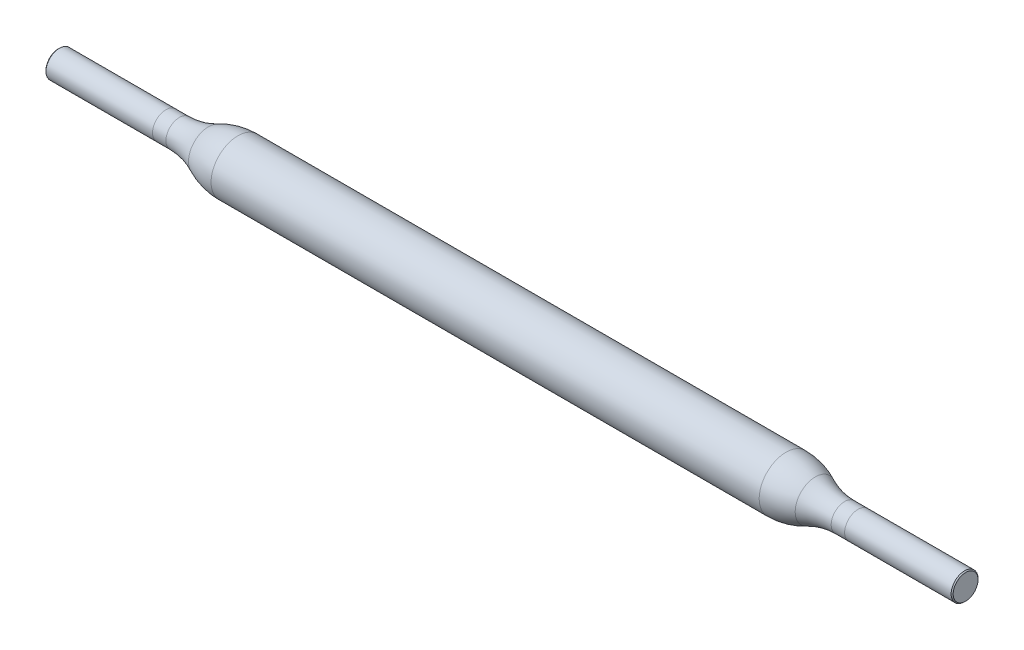
SolidWorks part; units mm, degrees
ref_plane "Front Plane" through (0, 0, 0) normal (0, 0, 1) x (1, 0, 0)
ref_plane "Top Plane" through (0, 0, 0) normal (0, 1, 0) x (1, 0, 0)
ref_plane "Right Plane" through (0, 0, 0) normal (1, 0, 0) x (0, 0, -1)
sketch "Sketch1" plane through (0, 0, 0) normal (0, 0, 1) x (1, 0, 0)
  line L0 (-33.75, 0) -> (33.75, 0)
  line L1 (33.75, 0) -> (33.75, 1)
  line L2 (-33.75, 0) -> (-33.75, 1)
  line L3 (-33.75, 1) -> (-24.75, 1)
  line L4 (-20.3911, 2) -> (20.3911, 2)
  line L5 (33.75, 1) -> (24.75, 1)
  line L6 (0, 0) -> (0, 10.5856) construction
  arc A0 (-24.75, 1) -> (-22.5706, 1.5) centre (-24.75, 6) ccw
  arc A1 (-20.3911, 2) -> (-22.5706, 1.5) centre (-20.3911, -3) ccw
  arc A2 (20.3911, 2) -> (22.5706, 1.5) centre (20.3911, -3) cw
  arc A3 (24.75, 1) -> (22.5706, 1.5) centre (24.75, 6) cw
  point P2 (0, 0)
  point P9 (0, 2)
  point P14 (-21.75, 2)
  dimension "D6" = 5
  dimension "D1" = 67.5
  dimension "D2" = 1
  dimension "D3" = 9
  dimension "D4" = 2
  dimension "D5" = 3
revolve "Revolve1" add sketch "Sketch1" angle 360 about L0
sketch "Sketch2" plane through (0, 0, 0) normal (0, 0, 1) x (1, 0, 0)
  line L0 (-25.75, 3.4753) -> (-25.75, -4.3442)
  line L1 (25.75, 4.2201) -> (25.75, -4.3442)
  line L2 (-33.75, 1) -> (-33.75, -1) construction
  line L3 (33.75, -1) -> (33.75, 1) construction
  dimension "D1" = 8
  dimension "D2" = 8.5642
  dimension "D3" = 8
split line "Split Line1"
chamfer "Chamfer1" distance 0.075 angle 45 2 edges at (-33.75, 0, 1) (33.75, 0, 1)
